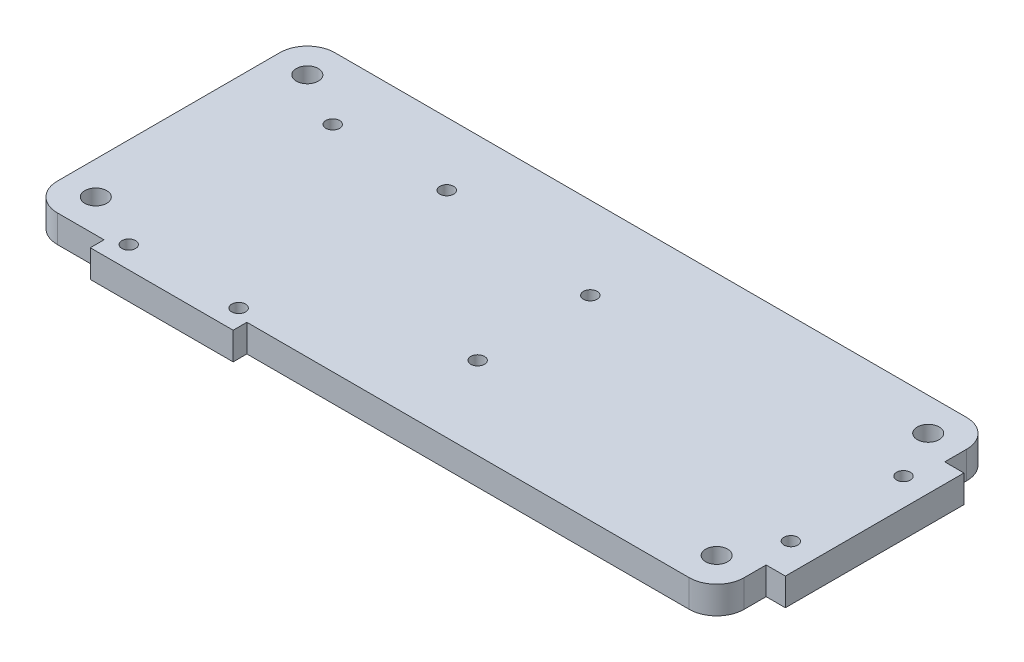
SolidWorks part; units mm, degrees
ref_plane "Front Plane" through (0, 0, 0) normal (0, 0, 1) x (1, 0, 0)
ref_plane "Top Plane" through (0, 0, 0) normal (0, 1, 0) x (1, 0, 0)
ref_plane "Right Plane" through (0, 0, 0) normal (1, 0, 0) x (0, 0, -1)
sketch "Sketch1" plane through (0, 0, 0) normal (0, 1, 0) x (1, 0, 0)
  line L0 (75.3425, 35.5) -> (75.3425, 50.5) construction
  line L1 (0, 0) -> (125, 0)
  line L2 (0, 0) -> (0, 50.5)
  line L3 (0, 50.5) -> (125, 50.5)
  line L4 (125, 0) -> (125, 50.5)
  line L5 (123.5, 35.5) -> (66.5, 35.5)
  line L6 (123.5, 35.5) -> (123.5, 15)
  line L7 (123.5, 15) -> (66.5, 15)
  line L8 (66.5, 35.5) -> (66.5, 15)
  line L9 (75.3425, 15) -> (75.3425, 0) construction
  line L10 (16.5, 1.5) -> (36.5, 1.5)
  line L15 (36.5, 1.5) -> (26.5, 1.5)
  line L16 (26.5, 1.5) -> (26.5, 39)
  line L17 (16.125, 39) -> (36.875, 39)
  line L18 (36.5, 1.5) -> (66.5, 1.5) construction
  line L19 (66.5, 1.5) -> (66.5, 15) construction
  line L20 (16.5, 1.5) -> (0, 1.5) construction
  line L21 (36.875, 39) -> (66.5, 39) construction
  line L22 (66.5, 39) -> (66.5, 35.5) construction
  line L23 (123.5, 25.25) -> (125, 25.25) construction
  line L25 (0, 50.5) -> (6, 50.5)
  line L26 (0, 50.5) -> (0, 44.5)
  line L27 (0, 44.5) -> (6, 44.5)
  line L28 (6, 50.5) -> (6, 44.5)
  line L29 (0, 0) -> (6, 0)
  line L30 (0, 0) -> (0, 6)
  line L31 (0, 6) -> (6, 6)
  line L32 (6, 0) -> (6, 6)
  line L33 (125, 0) -> (119, 0)
  line L34 (125, 0) -> (125, 6)
  line L35 (125, 6) -> (119, 6)
  line L36 (119, 0) -> (119, 6)
  line L37 (125, 50.5) -> (119, 50.5)
  line L38 (125, 50.5) -> (125, 44.5)
  line L39 (125, 44.5) -> (119, 44.5)
  line L40 (119, 50.5) -> (119, 44.5)
  circle A0 centre (66.5, 35.5) radius 1.25
  circle A1 centre (66.5, 15) radius 1.25
  circle A2 centre (123.5, 15) radius 1.25
  circle A3 centre (123.5, 35.5) radius 1.25
  circle A4 centre (16.5, 1.5) radius 1.25
  circle A5 centre (36.5, 1.5) radius 1.25
  circle A6 centre (16.125, 39) radius 1.25
  circle A7 centre (36.875, 39) radius 1.25
  circle A8 centre (6, 44.5) radius 2
  circle A9 centre (6, 6) radius 2
  circle A10 centre (119, 6) radius 2
  circle A11 centre (119, 44.5) radius 2
  point P23 (26.5, 39)
  dimension "D4" = 2.5
  dimension "D5" = 2.5
  dimension "D6" = 2.5
  dimension "D7" = 2.5
  dimension "D12" = 2.5
  dimension "D13" = 2.5
  dimension "D14" = 2.5
  dimension "D15" = 2.5
  dimension "D18" = 4
  dimension "D19" = 4
  dimension "D20" = 4
  dimension "D21" = 4
  dimension "D1" = 57
  dimension "D2" = 20.5
  dimension "D3" = 15
  dimension "D8" = 20
  dimension "D9" = 20.75
  dimension "D10" = 125
  dimension "D11" = 37.5
  dimension "D16" = 1.5
  dimension "D17" = 30
  dimension "D22" = 6
  dimension "D23" = 6
  dimension "D24" = 6
  dimension "D25" = 6
  dimension "D26" = 6
  dimension "D27" = 6
  dimension "D28" = 6
  dimension "D29" = 6
  dimension "D30" = 1.5
extrude "Boss-Extrude1" add sketch "Sketch1" along normal blind 5
fillet "Fillet1" radius 5 4 edges at (0, 2.5, -50.5) (125, 2.5, -50.5) (125, 2.5, 0) (0, 2.5, 0)
chamfer "Chamfer1" distance 1.5 angle 45 4 edges at (119, 0, -4) (119, 0, -42.5) (6, 0, -42.5) (6, 0, -4)
sketch "Hole Locations" plane through (0, 5, 0) normal (0, 1, 0) x (1, 0, 0)
  line L0 (6, 44.5) -> (119, 44.5) construction
  line L1 (119, 44.5) -> (119, 6) construction
  line L2 (119, 6) -> (6, 6) construction
  line L3 (6, 6) -> (6, 44.5) construction
sketch "Sketch3" plane through (0, 5, 0) normal (0, 1, 0) x (1, 0, 0)
  line L0 (125, 9) -> (128, 9)
  line L1 (125, 5) -> (125, 45.5) construction
  line L2 (128, 9) -> (128, 41.5)
  line L3 (128, 41.5) -> (125, 41.5)
  line L4 (120, 0) -> (128, 0) construction
  line L5 (128, 0) -> (128, 9) construction
  line L6 (120, 50.5) -> (128, 50.5) construction
  line L7 (128, 50.5) -> (128, 41.5) construction
  line L8 (5, 0) -> (120, 0) construction
  line L9 (13.5, 0) -> (39.5, 0)
  line L10 (13.5, 0) -> (13.5, -3)
  line L11 (13.5, -3) -> (39.5, -3)
  line L12 (39.5, 0) -> (39.5, -3)
  line L13 (16.5, 1.5) -> (13.5, 1.5) construction
  line L14 (13.5, 1.5) -> (13.5, 0) construction
  line L15 (36.5, 1.5) -> (39.5, 1.5) construction
  line L16 (39.5, 1.5) -> (39.5, 0) construction
  line L17 (125, 9) -> (125, 41.5)
  dimension "D1" = 3
  dimension "D2" = 9
  dimension "D3" = 9
  dimension "D4" = 3
  dimension "D5" = 3
  dimension "D6" = 3
extrude "Boss-Extrude2" add sketch "Sketch3" against normal blind 5
sketch "Sketch5" plane through (0, 0, 3) normal (0, 0, 1) x (1, 0, 0)
  line L1 (13.5, 5) -> (39.5, 5)
  line L2 (13.5, 5) -> (13.5, 0)
  line L3 (13.5, 0) -> (39.5, 0)
  line L4 (39.5, 5) -> (39.5, 0)
extrude "Cut-Extrude1" cut sketch "Sketch5" against normal blind 0.5
sketch "Sketch6" plane through (128, 0, 0) normal (1, 0, 0) x (0, 0, -1)
  line L1 (9, 5) -> (41.5, 5)
  line L2 (9, 5) -> (9, 0)
  line L3 (9, 0) -> (41.5, 0)
  line L4 (41.5, 5) -> (41.5, 0)
extrude "Boss-Extrude4" add sketch "Sketch6" along normal blind 0.5
